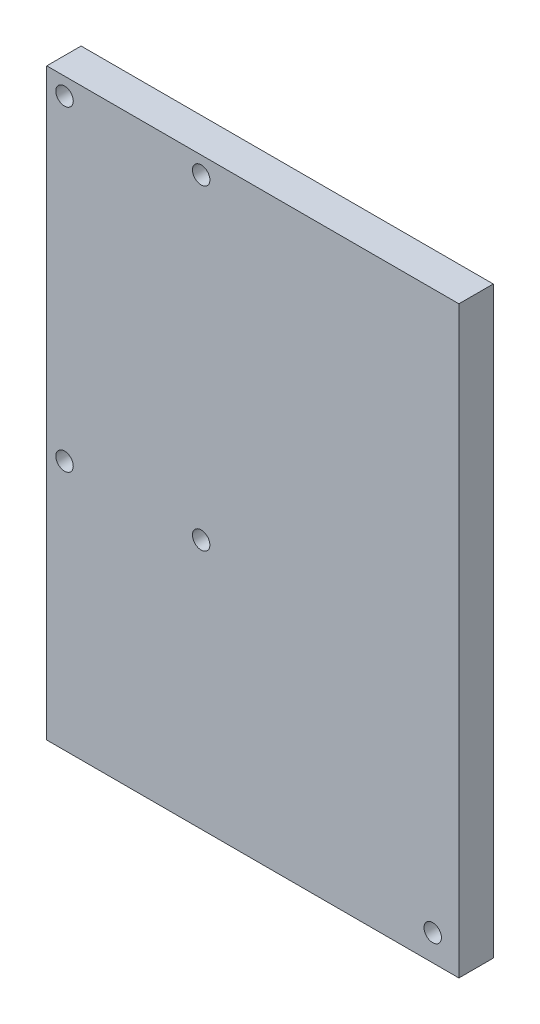
SolidWorks part; units mm, degrees
ref_plane "Front Plane" through (0, 0, 0) normal (0, 0, 1) x (1, 0, 0)
ref_plane "Top Plane" through (0, 0, 0) normal (0, 1, 0) x (1, 0, 0)
ref_plane "Right Plane" through (0, 0, 0) normal (1, 0, 0) x (0, 0, -1)
sketch "Sketch1" plane through (0, 0, 0) normal (0, 0, 1) x (1, 0, 0)
  line L0 (-13.9789, -33.4017) -> (-13.9789, -0.7627) construction
  line L1 (-12.5349, 25.527) -> (47.4651, 25.527)
  line L2 (-12.5349, 25.527) -> (-12.5349, -59.473)
  line L3 (-12.5349, -59.473) -> (47.4651, -59.473)
  line L4 (47.4651, 25.527) -> (47.4651, -59.473)
  line L5 (-13.9789, -33.4017) -> (-13.9789, -0.7627)
  line L6 (-17.5349, -28.6392) -> (-17.5349, -17.0822) construction
  line L7 (-17.5349, -28.6392) -> (-17.5349, -17.0822)
  line L8 (-12.5349, 25.527) -> (-12.5349, -25.527) construction
  line L9 (-4.45, 25.527) -> (-12.5349, 25.527) construction
  line L10 (-12.5349, 25.527) -> (-12.5349, -25.527)
  line L11 (-4.45, 25.527) -> (-12.5349, 25.527)
  dimension "D1" = 60
  dimension "D2" = 85
extrude "Boss-Extrude1" add sketch "Sketch1" along normal blind 5 contours L4 L3 L2 L1
sketch "Sketch2" plane through (0, 0, 5) normal (0, 0, 1) x (1, 0, 0)
  line L0 (-12.5349, -59.473) -> (47.4651, -59.473) construction
  line L1 (47.4651, -59.473) -> (47.4651, 25.527) construction
  circle A0 centre (9.9441, -23.0124) radius 1.27 construction
  circle A1 centre (-9.9441, -23.0124) radius 1.27 construction
  circle A2 centre (-9.9441, 23.0124) radius 1.27 construction
  circle A3 centre (9.9441, 23.0124) radius 1.27 construction
  circle A4 centre (9.9441, -23.0124) radius 1.27
  circle A5 centre (-9.9441, -23.0124) radius 1.27
  circle A6 centre (-9.9441, 23.0124) radius 1.27
  circle A7 centre (9.9441, 23.0124) radius 1.27
  circle A8 centre (43.6551, -55.663) radius 1.27
  dimension "D1" = 2.54
  dimension "D3" = 3.81
  dimension "D2" = 3.81
extrude "Cut-Extrude1" cut sketch "Sketch2" against normal blind 27
